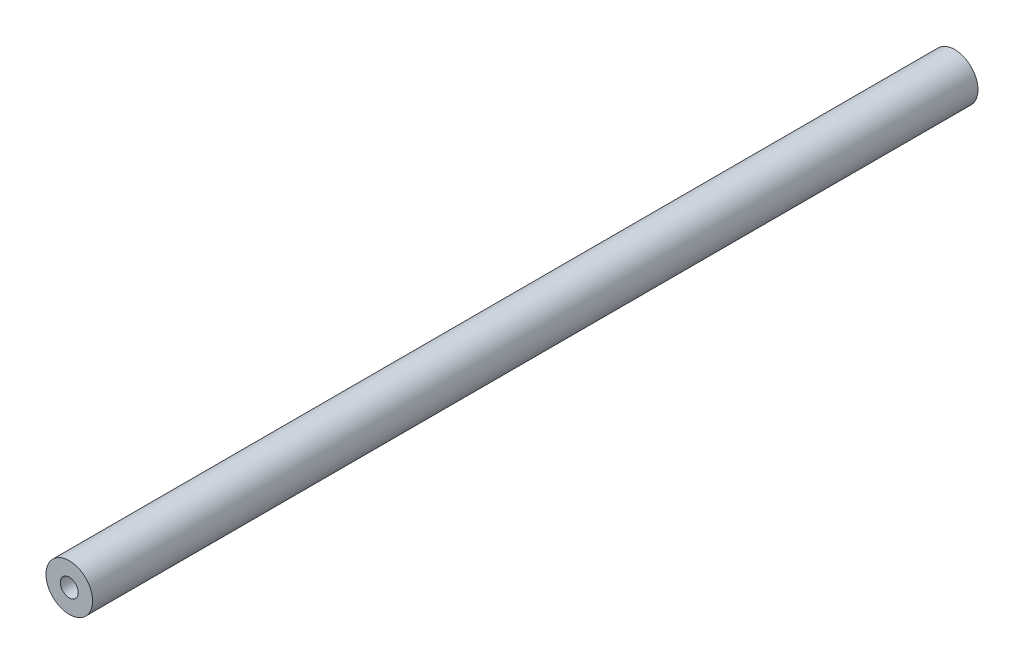
SolidWorks part; units mm, degrees
ref_plane "Front Plane" through (0, 0, 0) normal (0, 0, 1) x (1, 0, 0)
ref_plane "Top Plane" through (0, 0, 0) normal (0, 1, 0) x (1, 0, 0)
ref_plane "Right Plane" through (0, 0, 0) normal (1, 0, 0) x (0, 0, -1)
sketch "Sketch1" plane through (0, 0, 0) normal (0, 0, 1) x (1, 0, 0)
  circle A0 centre (0, 0) radius 3.25
  dimension "D1" = 6.5
extrude "Boss-Extrude1" add sketch "Sketch1" along normal blind 123.5
sketch "Sketch2" plane through (0, 0, 0) normal (0, 0, -1) x (-1, 0, 0)
  circle A0 centre (0, 0) radius 1.25
sketch "Sketch3" plane through (0, 0, 123.5) normal (0, 0, 1) x (1, 0, 0)
  circle A0 centre (0, 0) radius 1.25
  dimension "D1" = 2.5
extrude "Cut-Extrude1" cut sketch "Sketch3" against normal blind 10 contours A0
extrude "Cut-Extrude2" cut sketch "Sketch2" against normal blind 10 contours A0
